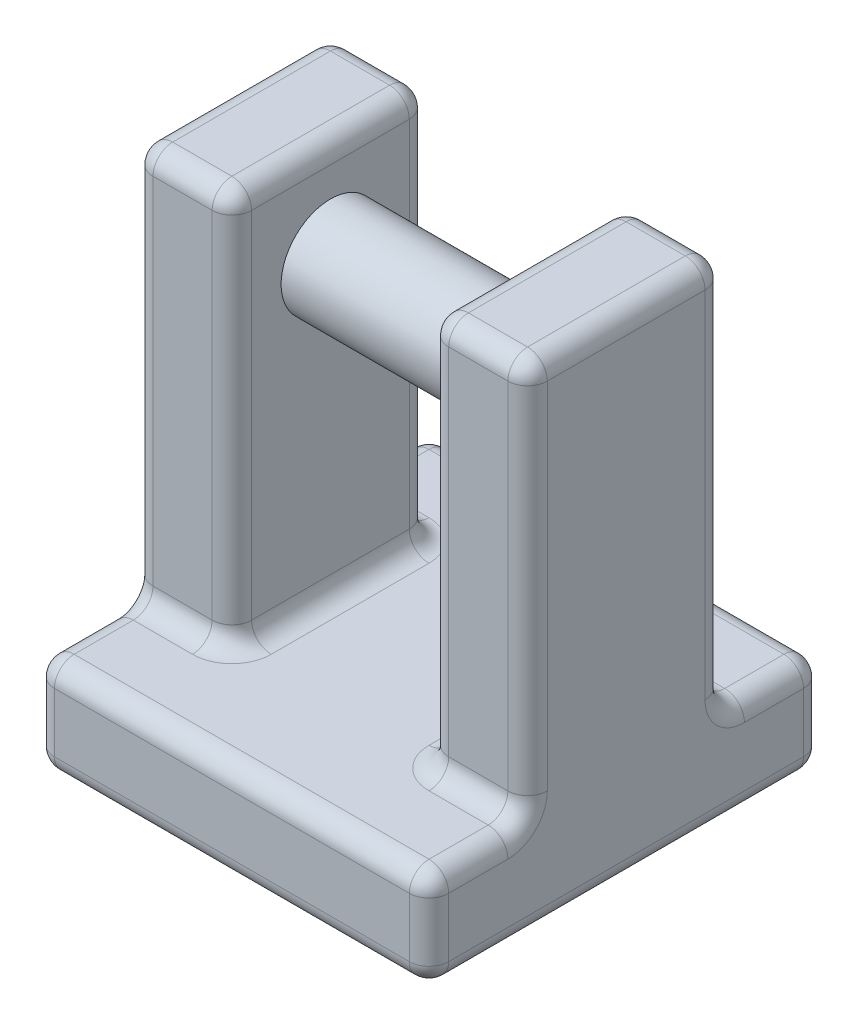
SolidWorks part; units mm, degrees
ref_plane "Alzado" through (0, 0, 0) normal (0, 0, 1) x (1, 0, 0)
ref_plane "Planta" through (0, 0, 0) normal (0, 1, 0) x (1, 0, 0)
ref_plane "Vista lateral" through (0, 0, 0) normal (1, 0, 0) x (0, 0, -1)
sketch "Croquis1" plane through (0, 0, 0) normal (0, 1, 0) x (1, 0, 0)
  line L1 (-10, 10) -> (10, 10)
  line L2 (-10, 10) -> (-10, -10)
  line L3 (-10, -10) -> (10, -10)
  line L4 (10, 10) -> (10, -10)
  point P4 (0, 10)
  point P6 (-10, 0)
  dimension "D1" = 20
  dimension "D2" = 20
extrude "Saliente-Extruir1" add sketch "Croquis1" along normal blind 5
sketch "Croquis2" plane through (0, 5, 0) normal (0, 1, 0) x (1, 0, 0)
  line L0 (-10, 10) -> (-10, -10) construction
  line L1 (-10, 5) -> (-5, 5)
  line L2 (-10, 5) -> (-10, -5)
  line L3 (-10, -5) -> (-5, -5)
  line L4 (-5, 5) -> (-5, -5)
  line L5 (10, -10) -> (10, 10) construction
  line L6 (5, 5) -> (10, 5)
  line L7 (5, 5) -> (5, -5)
  line L8 (5, -5) -> (10, -5)
  line L9 (10, 5) -> (10, -5)
  point P12 (-10, 0)
  point P14 (10, 0)
  dimension "D1" = 5
  dimension "D2" = 5
  dimension "D3" = 10
  dimension "D4" = 10
extrude "Saliente-Extruir2" add sketch "Croquis2" along normal blind 20
sketch "Croquis3" plane through (5, 0, 0) normal (-1, 0, 0) x (0, 0, 1)
  line L0 (-5, 25) -> (5, 25) construction
  circle A0 centre (0, 20) radius 2.5
  point P4 (0, 0)
  point P5 (0, 25)
  dimension "D1" = 5
extrude "Saliente-Extruir3" add sketch "Croquis3" along normal up to next
fillet "Redondeo4" radius 1 36 edges at (0, 0, 10) (-10, 2.5, -10) (0, 0, -10) (10, 2.5, -10) (10, 5, -7.5) (10, 0, 0) (10, 2.5, 10) (10, 5, 7.5) (-5, 5, 0) (0, 5, -10) (-10, 0, 0) (-10, 5, -7.5) (-10, 2.5, 10) (0, 5, 10) (-10, 5, 7.5) (5, 5, 0) (10, 15, -5) (-5, 15, -5) (-7.5, 5, -5) (7.5, 5, 5) (-7.5, 5, 5) (-5, 15, 5) (-10, 15, 5) (-10, 15, -5) (5, 15, -5) (10, 15, 5) (5, 15, 5) (7.5, 5, -5) (7.5, 25, 5) (10, 25, 0) (7.5, 25, -5) (5, 25, 0) (-7.5, 25, 5) (-5, 25, 0) (-10, 25, 0) (-7.5, 25, -5)
